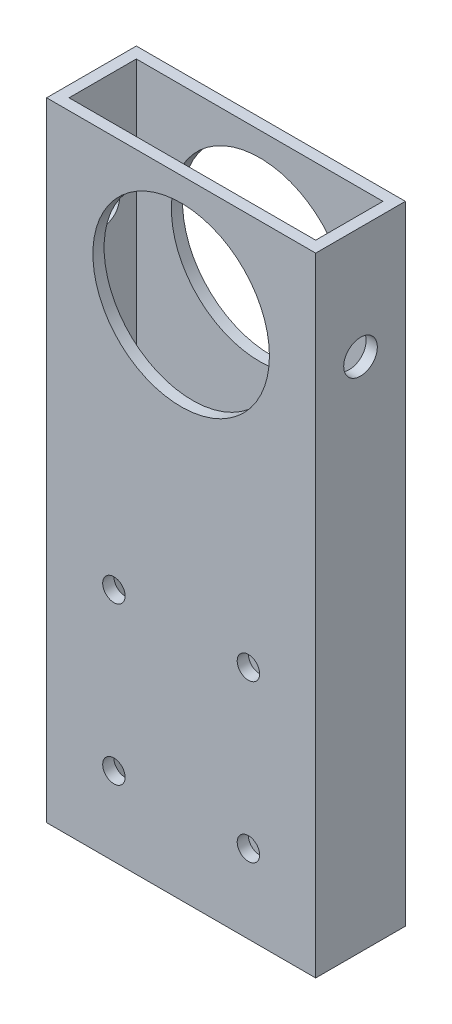
SolidWorks part; units mm, degrees
material "1060 Alloy"
ref_plane "Front Plane" through (0, 0, 0) normal (0, 0, 1) x (1, 0, 0)
ref_plane "Top Plane" through (0, 0, 0) normal (0, 1, 0) x (1, 0, 0)
ref_plane "Right Plane" through (0, 0, 0) normal (1, 0, 0) x (0, 0, -1)
sketch "Sketch1" plane through (0, 0, 0) normal (0, 1, 0) x (1, 0, 0)
  line L0 (34.925, 9.525) -> (-34.925, 9.525)
  line L1 (38.1, -12.7) -> (-38.1, -12.7)
  line L2 (38.1, -12.7) -> (38.1, 12.7)
  line L3 (38.1, 12.7) -> (-38.1, 12.7)
  line L4 (-38.1, -12.7) -> (-38.1, 12.7)
  line L5 (38.1, -12.7) -> (-38.1, 12.7) construction
  line L6 (38.1, 12.7) -> (-38.1, -12.7) construction
  line L7 (-34.925, -9.525) -> (-34.925, 9.525)
  line L8 (34.925, -9.525) -> (-34.925, -9.525)
  line L9 (34.925, -9.525) -> (34.925, 9.525)
  point P0 (0, 0)
  dimension "D1" = 76.2
  dimension "D2" = 25.4
  dimension "D3" = 3.175
extrude "Boss-Extrude1" add sketch "Sketch1" along normal blind 177.8
sketch "Sketch2" plane through (0, 0, 12.7) normal (0, 0, 1) x (1, 0, 0)
  line L0 (0, 177.8) -> (0, 146.05) construction
  line L1 (-38.1, 177.8) -> (38.1, 177.8) construction
  circle A0 centre (0, 146.05) radius 25
  dimension "D1" = 50
  dimension "D2" = 31.75
extrude "Cut-Extrude1" cut sketch "Sketch2" against normal through all
sketch "Sketch3" plane through (-38.1, 0, 0) normal (-1, 0, 0) x (0, 0, 1)
  line L0 (11.1125, 171.05) -> (11.1125, 121.05) construction
  line L1 (12.7, 171.05) -> (9.525, 171.05) construction
  line L2 (9.525, 121.05) -> (12.7, 121.05) construction
  line L3 (-11.1125, 171.05) -> (-11.1125, 121.05) construction
  line L4 (-9.525, 171.05) -> (-12.7, 171.05) construction
  line L5 (-12.7, 121.05) -> (-9.525, 121.05) construction
  line L6 (12.7, 146.05) -> (-12.7, 146.05)
  line L7 (12.7, 177.8) -> (12.7, 0) construction
  line L8 (-12.7, 177.8) -> (-12.7, 0) construction
  circle A0 centre (0, 146.05) radius 4.7625
  point P18 (11.1125, 146.05)
  dimension "D1" = 9.525
extrude "Cut-Extrude2" cut sketch "Sketch3" against normal through all both and the other way through all contours A0
sketch "Sketch4" plane through (0, 0, 12.7) normal (0, 0, 1) x (1, 0, 0)
  line L1 (-38.1, 177.8) -> (-38.1, 0) construction
  line L2 (-38.1, 88.9) -> (0, 44.45) construction
  line L3 (0, 44.45) -> (38.1, 0) construction
  line L4 (38.1, 0) -> (-38.1, 0) construction
  line L5 (-38.1, 0) -> (0, 44.45) construction
  line L6 (0, 44.45) -> (38.1, 88.9) construction
  line L7 (38.1, 177.8) -> (38.1, 0) construction
  circle A0 centre (-19.05, 66.675) radius 3.175
  circle A1 centre (19.05, 66.675) radius 3.175
  circle A2 centre (19.05, 22.225) radius 3.175
  circle A3 centre (-19.05, 22.225) radius 3.175
  dimension "D1" = 6.35
  dimension "D2" = 6.35
  dimension "D3" = 6.35
  dimension "D4" = 6.35
extrude "Cut-Extrude3" cut sketch "Sketch4" against normal through all both and the other way through all
